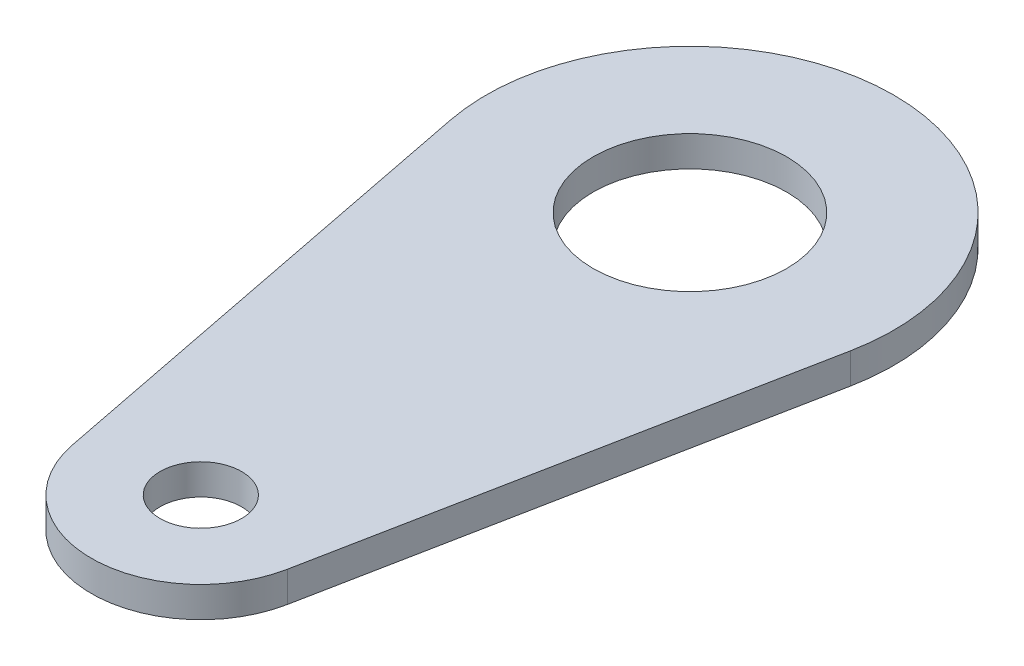
SolidWorks part; units mm, degrees
material "Galvanized Steel"
ref_plane "Front Plane" through (0, 0, 0) normal (0, 0, 1) x (1, 0, 0)
ref_plane "Top Plane" through (0, 0, 0) normal (0, 1, 0) x (1, 0, 0)
ref_plane "Right Plane" through (0, 0, 0) normal (1, 0, 0) x (0, 0, -1)
sketch "Sketch1" plane through (0, 0, 0) normal (0, 1, 0) x (1, 0, 0)
  line L0 (-13663.0749, 3210.0679) -> (-13663.075, 3198.068)
  line L1 (-13651.0749, 3210.0679) -> (-13663.0749, 3210.0679)
  line L2 (-13651.075, 3198.0679) -> (-13651.0749, 3210.0679)
  line L3 (-13663.075, 3198.068) -> (-13651.075, 3198.0679)
  line L4 (-13646.5196, 3154.0153) -> (-13637.4496, 3200.215)
  line L5 (-13667.6303, 3154.0153) -> (-13676.7003, 3200.215)
  arc A0 (-13637.4496, 3200.215) -> (-13676.7003, 3200.215) centre (-13657.0749, 3204.0679) ccw
  arc A1 (-13667.6303, 3154.0153) -> (-13646.5196, 3154.0153) centre (-13657.0749, 3156.0679) ccw
  circle A2 centre (-13657.0749, 3156.0679) radius 4
  circle A3 centre (-13657.0749, 3156.0679) radius 4
extrude "Boss-Extrude1" add sketch "Sketch1" along normal blind 3 contours L5 A1 L4 A0 A2 L3 L0 L1 L2
sketch "Sketch2" plane through (0, 0, 0) normal (0, -1, 0) x (1, 0, 0)
  line L3 (-13667.2249, -3214.2179) -> (-13646.9249, -3214.2179)
  line L4 (-13667.2249, -3214.2179) -> (-13667.2249, -3193.9179)
  line L5 (-13667.2249, -3193.9179) -> (-13646.9249, -3193.9179)
  line L6 (-13646.9249, -3214.2179) -> (-13646.9249, -3193.9179)
  point P8 (-13657.0749, -3204.0679)
  dimension "D1" = 20.3
  dimension "D2" = 20.3
sketch "Sketch3" plane through (0, 0, 0) normal (0, -1, 0) x (1, 0, 0)
  circle A0 centre (-13657.0749, -3204.0679) radius 9.5
  dimension "D1" = 19
extrude "Cut-Extrude3" cut sketch "Sketch3" against normal through all both and the other way through all
